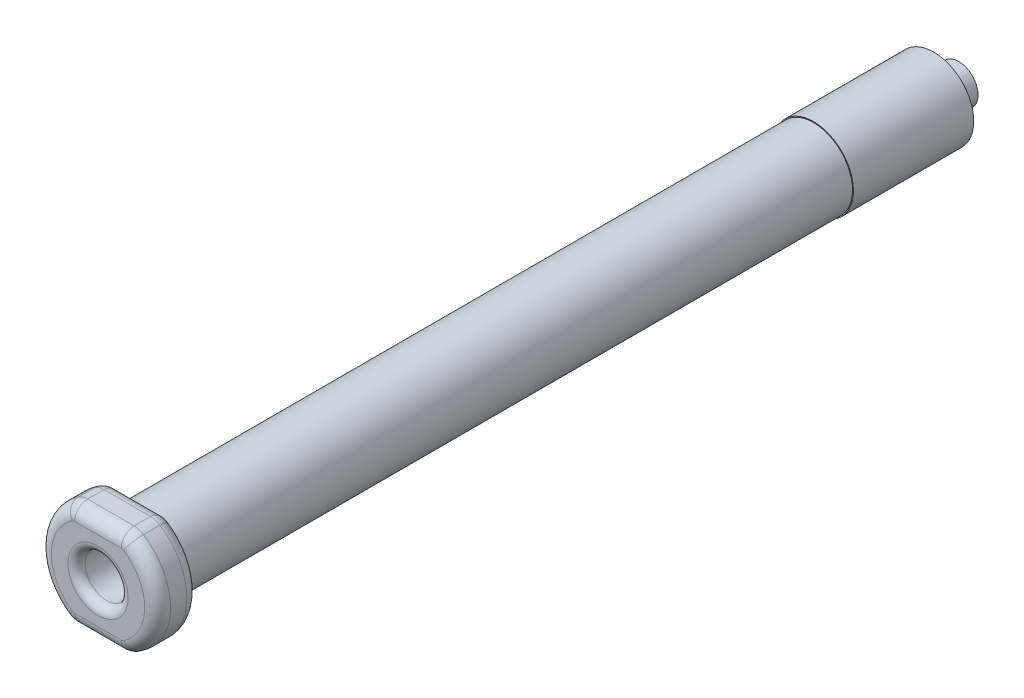
SolidWorks part; units mm, degrees
material "Glass"
ref_plane "Front Plane" through (0, 0, 0) normal (0, 0, 1) x (1, 0, 0)
ref_plane "Top Plane" through (0, 0, 0) normal (0, 1, 0) x (1, 0, 0)
ref_plane "Right Plane" through (0, 0, 0) normal (1, 0, 0) x (0, 0, -1)
sketch "Sketch1" plane through (0, 0, 0) normal (0, 0, 1) x (1, 0, 0)
  circle A0 centre (0, 0) radius 4.55
  dimension "D1" = 9.1
extrude "Boss-Extrude1" add sketch "Sketch1" along normal blind 83.25
sketch "Sketch2" plane through (0, 0, 83.25) normal (0, 0, 1) x (1, 0, 0)
  line L0 (-3.25, 6.125) -> (3.25, 6.125)
  line L1 (-3.25, -6.125) -> (3.25, -6.125)
  arc A0 (3.25, 6.125) -> (3.25, -6.125) centre (0, 0) cw
  arc A1 (-3.25, 6.125) -> (-3.25, -6.125) centre (0, 0) ccw
  point P4 (0, 6.125)
  point P5 (0, -6.125)
  point P9 (-6.9338, 0)
  dimension "D1" = 6.125
  dimension "D2" = 6.125
  dimension "D3" = 6.5
  dimension "D4" = 3.6838
extrude "Boss-Extrude2" add sketch "Sketch2" against normal blind 4.9
sketch "Sketch3" plane through (0, 0, 0) normal (0, 0, -1) x (-1, 0, 0)
  circle A0 centre (0, 0) radius 4.65
  dimension "D1" = 9.3
extrude "Boss-Extrude3" add sketch "Sketch3" along normal blind 14
sketch "Sketch4" plane through (0, 0, -14) normal (0, 0, -1) x (-1, 0, 0)
  circle A0 centre (0, 0) radius 4.5
  dimension "D1" = 9
extrude "Cut-Extrude1" cut sketch "Sketch4" against normal blind 14
sketch "Sketch5" plane through (0, 0, 0) normal (0, 0, -1) x (-1, 0, 0)
  circle A0 centre (0, 0) radius 2.25
  dimension "D1" = 4.5
extrude "Boss-Extrude4" add sketch "Sketch5" along normal blind 16.9
sketch "Sketch6" plane through (0, 0, -16.9) normal (0, 0, -1) x (-1, 0, 0)
  circle A0 centre (0, 0) radius 0.875
  dimension "D1" = 1.75
extrude "Cut-Extrude2" cut sketch "Sketch6" against normal blind 16.9
sketch "Sketch7" plane through (0, 0, 83.25) normal (0, 0, 1) x (1, 0, 0)
  circle A0 centre (0, 0) radius 2.5
  dimension "D1" = 5
extrude "Cut-Extrude3" cut sketch "Sketch7" against normal up to surface (83.25 mm away) up to face at (4.55, 0, 0)
fillet "Fillet4" radius 2 4 edges at (-3.25, -6.125, 80.8) (3.25, -6.125, 80.8) (3.25, 6.125, 80.8) (-3.25, 6.125, 80.8)
fillet "Fillet5" radius 1.5 8 edges at (3.2795, -6.0413, 83.25) (0, -6.125, 83.25) (-3.2795, -6.0413, 83.25) (-6.9338, 0, 83.25) (-3.2795, 6.0413, 83.25) (0, 6.125, 83.25) (3.2795, 6.0413, 83.25) (6.9338, 0, 83.25)
fillet "Fillet6" radius 1.5 8 edges at (3.2795, -6.0413, 78.35) (0, -6.125, 78.35) (-3.2795, -6.0413, 78.35) (-6.9338, 0, 78.35) (-3.2795, 6.0413, 78.35) (0, 6.125, 78.35) (3.2795, 6.0413, 78.35) (6.9338, 0, 78.35)
fillet "Fillet7" radius 1 1 edges at (2.5, 0, 83.25)
